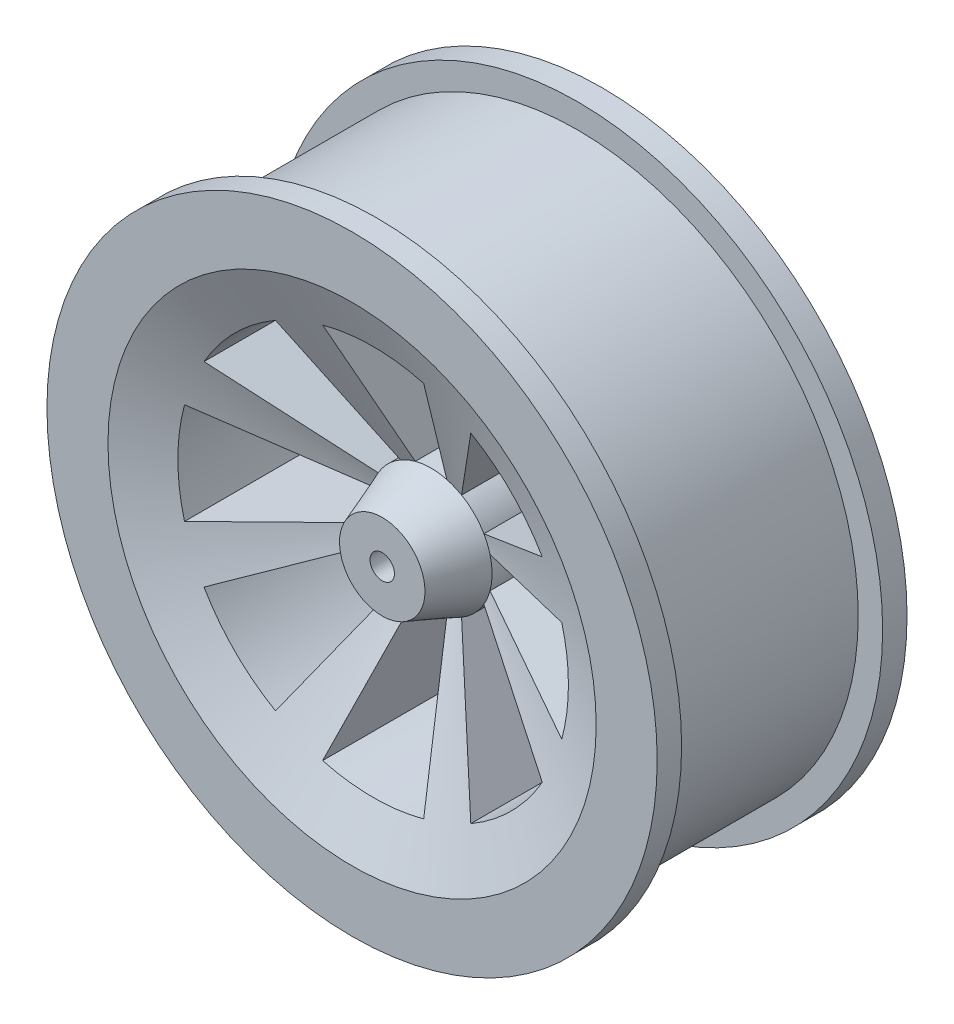
SolidWorks part; units mm, degrees
ref_plane "Front Plane" through (0, 0, 0) normal (0, 0, 1) x (1, 0, 0)
ref_plane "Top Plane" through (0, 0, 0) normal (0, 1, 0) x (1, 0, 0)
ref_plane "Right Plane" through (0, 0, 0) normal (1, 0, 0) x (0, 0, -1)
sketch "Sketch1" plane through (0, 0, 0) normal (1, 0, 0) x (0, 0, -1)
  line L0 (-8.89, 1.27) -> (3.81, 1.27)
  line L3 (3.81, 6.35) -> (13.97, 25.4)
  line L4 (13.97, 25.4) -> (13.97, 31.75)
  line L5 (13.97, 31.75) -> (11.43, 31.75)
  line L6 (11.43, 31.75) -> (11.43, 29.21)
  line L7 (11.43, 29.21) -> (-9.49, 29.21)
  line L8 (-9.49, 29.21) -> (-9.49, 31.75)
  line L9 (-9.49, 31.75) -> (-12.03, 31.75)
  line L10 (-12.03, 31.75) -> (-12.03, 25.4)
  line L11 (-12.03, 25.4) -> (-3.81, 6.35)
  line L12 (-3.81, 6.35) -> (-8.89, 4.445)
  line L13 (-8.89, 4.445) -> (-8.89, 1.27)
  line L14 (3.81, 6.35) -> (-3.81, 6.35) construction
  line L15 (0, 0) -> (15.955, 0) construction
  line L16 (3.81, 6.35) -> (3.81, 1.27)
  point P1 (3.81, 29.21)
  point P5 (0, 0)
  point P9 (0, 6.35)
  dimension "D1" = 1.27
  dimension "D2" = 5.08
  dimension "D3" = 3.175
  dimension "D4" = 31.75
  dimension "D5" = 26
  dimension "D6" = 2.54
  dimension "D7" = 2.54
  dimension "D8" = 6.35
  dimension "D9" = 7.62
  dimension "D10" = 7.62
  dimension "D11" = 19.05
revolve "Revolve1" add sketch "Sketch1" angle 360 about L15
sketch "Sketch2" plane through (0, 0, 12.03) normal (0, 0, 1) x (1, 0, 0)
  line L0 (-5.2592, 19.6276) -> (-1.6435, 6.1336)
  line L1 (5.2592, 19.6276) -> (1.6435, 6.1336)
  circle A0 centre (0, 0) radius 25.4 construction
  circle A1 centre (0, 0) radius 25.4 construction
  arc A2 (-5.2592, 19.6276) -> (5.2592, 19.6276) centre (0, 0) cw
  arc A3 (-1.6435, 6.1336) -> (1.6435, 6.1336) centre (0, 0) cw
  point P7 (0, 20.32)
  point P11 (0, 6.35)
  dimension "D1" = 20.32
  dimension "D3" = 6.35
  dimension "D2" = 30
  dimension "D4" = 30
extrude "Cut-Extrude1" cut sketch "Sketch2" against normal up to surface (23.2907 mm away)
pattern_circular "CirPattern1" count 8 over 360 about axis through (0, 0, 0) along (0, 0, 1) of "Cut-Extrude1"
